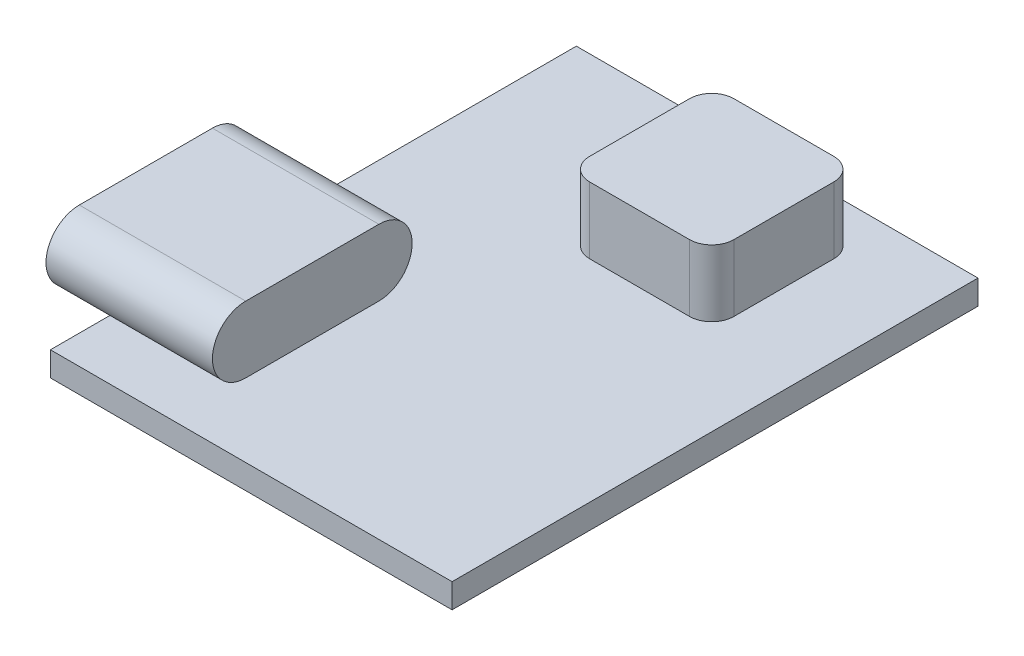
SolidWorks part; units mm, degrees
material "ABS"
ref_plane "Front Plane" through (0, 0, 0) normal (0, 0, 1) x (1, 0, 0)
ref_plane "Top Plane" through (0, 0, 0) normal (0, 1, 0) x (1, 0, 0)
ref_plane "Right Plane" through (0, 0, 0) normal (1, 0, 0) x (0, 0, -1)
sketch "Sketch1" plane through (0, 0, 0) normal (0, 1, 0) x (1, 0, 0)
  line L1 (-9.05, 11.85) -> (9.05, 11.85)
  line L2 (-9.05, 11.85) -> (-9.05, -11.85)
  line L3 (-9.05, -11.85) -> (9.05, -11.85)
  line L4 (9.05, 11.85) -> (9.05, -11.85)
  line L5 (0, -11.85) -> (0, 11.85) construction
  line L6 (-9.05, 0) -> (9.05, 0) construction
  point P0 (0, 0)
  dimension "D1" = 18.1
  dimension "D2" = 23.7
extrude "Boss-Extrude1" add sketch "Sketch1" along normal blind 1.1
sketch "Sketch3" plane through (-9.05, 0, 0) normal (-1, 0, 0) x (0, 0, 1)
  line L0 (2.55, 2.6) -> (8.55, 2.6) construction
  line L1 (2.55, 4.1) -> (8.55, 4.1)
  line L2 (2.55, 1.1) -> (8.55, 1.1)
  line L3 (-11.85, 1.1) -> (11.85, 1.1) construction
  line L4 (11.85, 1.1) -> (11.85, 0) construction
  arc A0 (2.55, 4.1) -> (2.55, 1.1) centre (2.55, 2.6) ccw
  arc A1 (8.55, 1.1) -> (8.55, 4.1) centre (8.55, 2.6) ccw
  point P2 (5.55, 2.6)
  point P7 (1.05, 2.6)
  point P8 (10.05, 2.6)
  dimension "D1" = 9
  dimension "D2" = 3
  dimension "D3" = 6.3
extrude "Boss-Extrude2" add sketch "Sketch3" along normal blind 2 and the other way blind 5.5 separate body
shell "Shell1" thickness 0.3
sketch "Sketch4" plane through (0, 1.1, 0) normal (0, 1, 0) x (1, 0, 0)
  line L0 (9.05, 11.85) -> (-9.05, 11.85) construction
  line L1 (-1.45, 10.35) -> (5.05, 10.35)
  line L2 (-1.45, 10.35) -> (-1.45, 3.85)
  line L3 (-1.45, 3.85) -> (5.05, 3.85)
  line L4 (5.05, 10.35) -> (5.05, 3.85)
  line L5 (9.05, -11.85) -> (9.05, 11.85) construction
  dimension "D1" = 6.5
  dimension "D2" = 1.5
  dimension "D3" = 4
extrude "Boss-Extrude3" add sketch "Sketch4" along normal blind 3 separate body
fillet "Fillet1" radius 1 4 edges at (5.05, 2.6, -10.35) (-1.45, 2.6, -10.35) (-1.45, 2.6, -3.85) (5.05, 2.6, -3.85)
